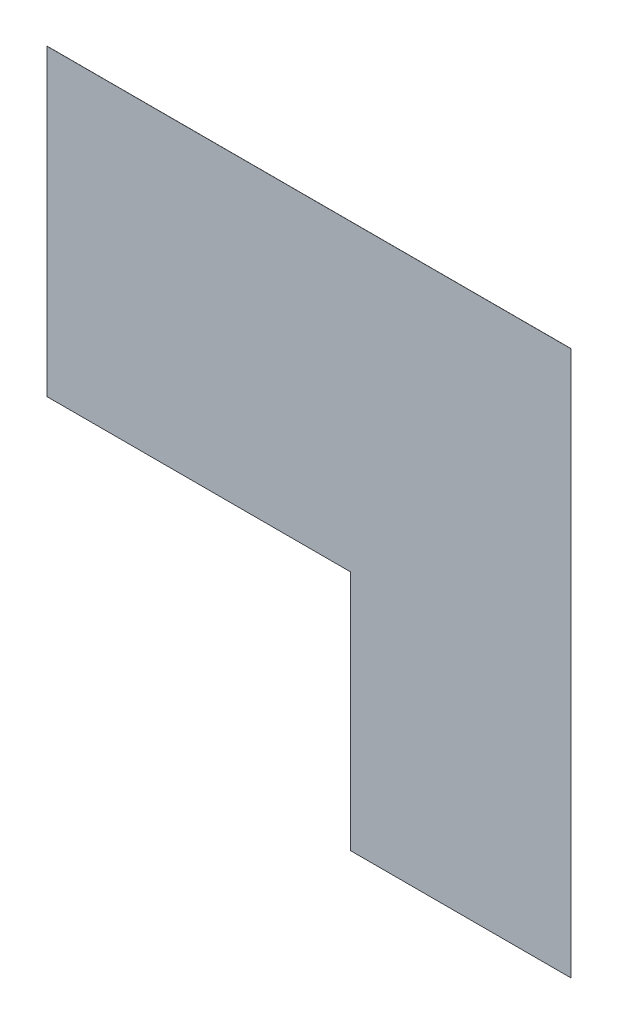
SolidWorks part; units mm, degrees
ref_plane "Front Plane" through (0, 0, 0) normal (0, 0, 1) x (1, 0, 0)
ref_plane "Top Plane" through (0, 0, 0) normal (0, 1, 0) x (1, 0, 0)
ref_plane "Right Plane" through (0, 0, 0) normal (1, 0, 0) x (0, 0, -1)
sketch "Sketch1" plane through (0, 0, 0) normal (0, 0, 1) x (1, 0, 0)
  line L0 (0, 0) -> (0, 69.85)
  line L1 (0, 69.85) -> (120.65, 69.85)
  line L2 (120.65, 69.85) -> (120.65, 0)
  line L3 (120.65, 0) -> (0, 0)
extrude "Boss-Extrude1" add sketch "Sketch1" along normal blind 0.0254
sketch "Sketch2" plane through (0, 0, 0.0254) normal (0, 0, 1) x (1, 0, 0)
  line L0 (120.65, 0) -> (120.65, -55.5625)
  line L1 (120.65, -55.5625) -> (69.85, -55.5625)
  line L2 (69.85, -55.5625) -> (69.85, 0)
  line L3 (0, 0) -> (120.65, 0) construction
  line L4 (69.85, 0) -> (120.65, 0)
extrude "Boss-Extrude2" add sketch "Sketch2" against normal blind 0.0254
